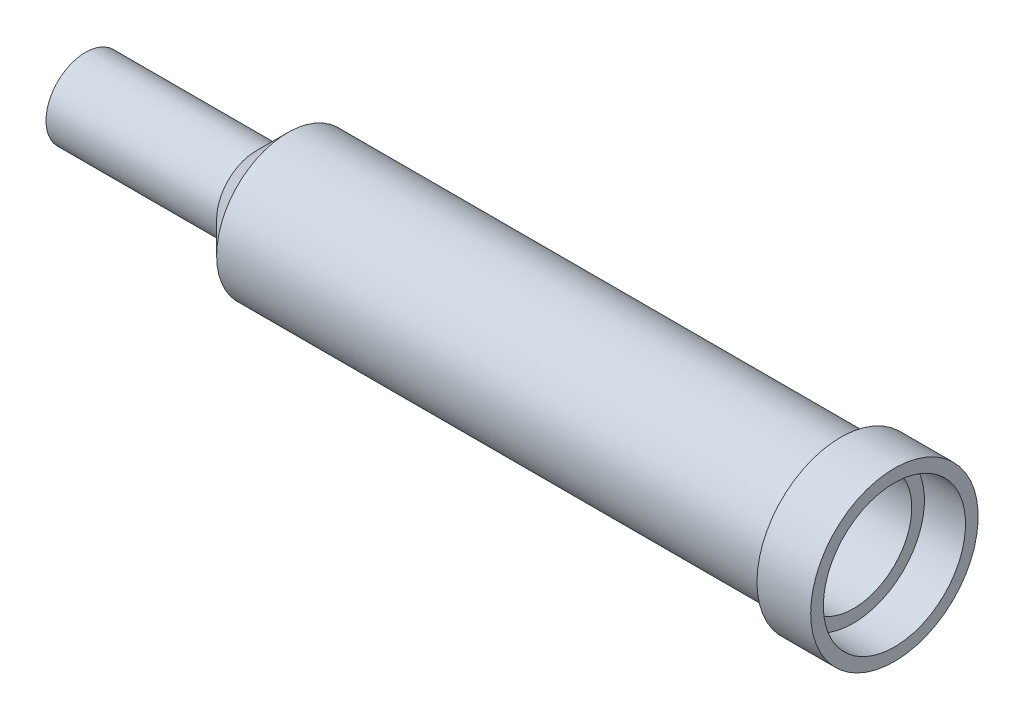
SolidWorks part; units mm, degrees
ref_plane "Front" through (0, 0, 0) normal (0, 0, 1) x (1, 0, 0)
ref_plane "Top" through (0, 0, 0) normal (0, 1, 0) x (1, 0, 0)
ref_plane "Right" through (0, 0, 0) normal (1, 0, 0) x (0, 0, -1)
sketch "Sketch1" plane through (0, 0, 0) normal (0, 1, 0) x (1, 0, 0)
  line L0 (-52.1171, 0) -> (59.7697, 0) construction
  line L1 (-25.6, 0.85) -> (-20.0343, 0.85)
  line L2 (-25.6, 1.25) -> (-20.2, 1.25)
  line L3 (-20.2, 1.25) -> (-19.2, 2.25)
  line L4 (-19.2, 2.25) -> (-1.7, 2.25)
  line L5 (-1.7, 2.25) -> (-1.7, 2.65)
  line L6 (-1.7, 2.65) -> (0, 2.65)
  line L7 (-20.0343, 0.85) -> (-19.0343, 1.85)
  line L8 (-19.0343, 1.85) -> (-1.3, 1.85)
  line L9 (-1.3, 1.85) -> (-1.3, 2.25)
  line L10 (-1.3, 2.25) -> (0, 2.25)
  line L11 (-25.6, 1.25) -> (-25.6, 0.85)
  line L12 (0, 2.65) -> (0, 2.25)
  dimension "D1" = 0.4
  dimension "D2" = 1.7
  dimension "D3" = 4.5
  dimension "D4" = 2.5
  dimension "D5" = 17.5
  dimension "D6" = 45
  dimension "D7" = 5.3
  dimension "D8" = 25.6
revolve "Revolve1" add sketch "Sketch1" angle 360 about L0
